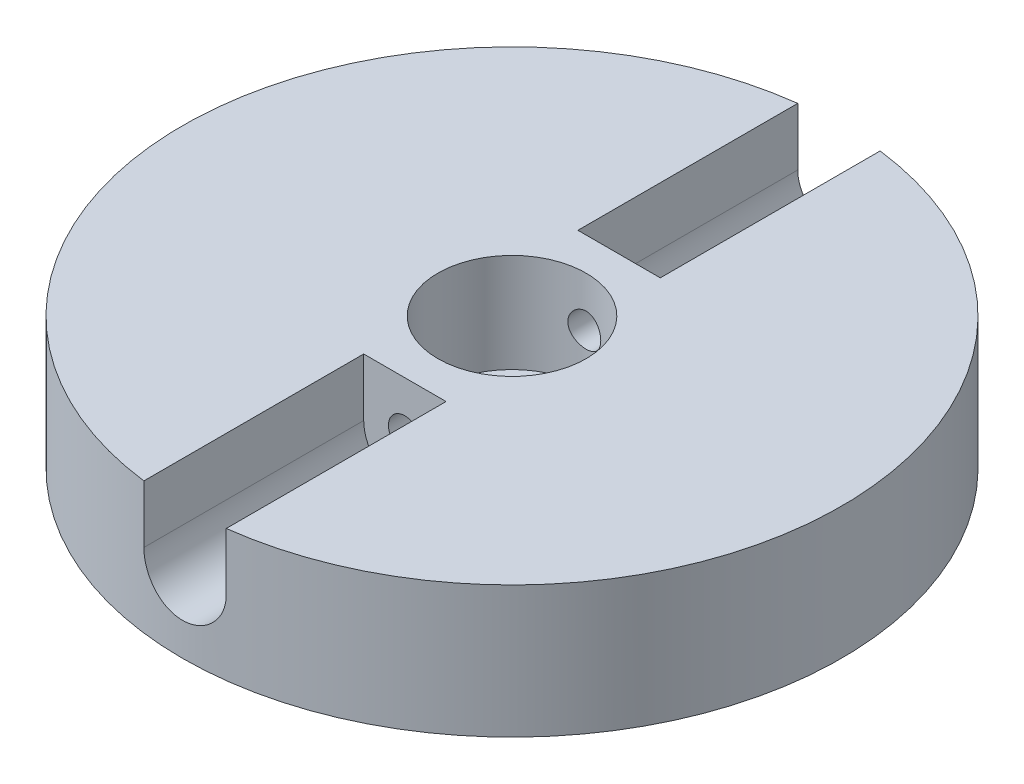
SolidWorks part; units mm, degrees
ref_plane "Front Plane" through (0, 0, 0) normal (0, 0, 1) x (1, 0, 0)
ref_plane "Top Plane" through (0, 0, 0) normal (0, 1, 0) x (1, 0, 0)
ref_plane "Right Plane" through (0, 0, 0) normal (1, 0, 0) x (0, 0, -1)
sketch "Sketch2" plane through (0, 0, 0) normal (0, 1, 0) x (1, 0, 0)
  circle A0 centre (0, 0) radius 20
  dimension "D1" = 40
extrude "Boss-Extrude1" add sketch "Sketch2" along normal blind 8
sketch "Sketch3" plane through (0, 8, 0) normal (0, 1, 0) x (1, 0, 0)
  circle A0 centre (0, 0) radius 12.5
  circle A1 centre (0, 0) radius 4.5
  dimension "D1" = 25
  dimension "D2" = 9
ref_plane "Plane1" through (0, 0, 4.5) normal (0, 0, 1) x (1, 0, 0)
sketch "Sketch7" plane through (0, 0, 4.5) normal (0, 0, 1) x (1, 0, 0)
  line L0 (0, 0) -> (0, 5)
  circle A0 centre (0, 5) radius 1
  dimension "D1" = 5
extrude "Cut-Extrude7" cut sketch "Sketch7" along normal through all both and the other way through all
ref_plane "Plane2" through (0, 0, 20) normal (0, 0, 1) x (1, 0, 0)
ref_plane "Plane3" through (0, 0, -6.5) normal (0, 0, 1) x (1, 0, 0)
sketch "Sketch9" plane through (0, 0, 20) normal (0, 0, 1) x (1, 0, 0)
  line L0 (2.5, 0) -> (2.5, 2)
  line L1 (0, 0) -> (2.5, 0)
  line L2 (0, 0) -> (0, 8)
  line L3 (0, 8) -> (2.5, 8)
  line L4 (2.5, 0) -> (2.5, 8)
  line L5 (0, 8) -> (-2.5, 8)
  line L6 (-2.5, 8) -> (-2.5, 0)
  line L7 (-2.5, 0) -> (0, 0)
  line L8 (2.5, 2) -> (-2.5, 2)
  arc A0 (-2.5, 4.5) -> (2.5, 4.5) centre (0, 4.5) ccw
  dimension "D6" = 2.5
  dimension "D1" = 2
  dimension "D2" = 8
  dimension "D3" = 2.5
  dimension "D4" = 8
  dimension "D5" = 2.5
extrude "Cut-Extrude8" cut sketch "Sketch9" against normal blind 13.5 contours L8 L2 L5 L6 | L8 L4 L3 L2
sketch "Sketch10" plane through (0, 0, -6.5) normal (0, 0, 1) x (1, 0, 0)
  line L1 (0, 0) -> (-2.5, 0)
  line L2 (0, 0) -> (0, 8)
  line L3 (0, 8) -> (-2.5, 8)
  line L4 (-2.5, 0) -> (-2.5, 8)
  line L5 (0, 0) -> (2.5, 0)
  line L6 (0, 0) -> (0, 8)
  line L7 (0, 8) -> (2.5, 8)
  line L8 (2.5, 0) -> (2.5, 8)
  arc A0 (-2.5, 4.5) -> (2.5, 4.5) centre (0, 4.5) ccw
  dimension "D5" = 4.5
  dimension "D1" = 8
  dimension "D2" = 2.5
  dimension "D3" = 2.5
  dimension "D4" = 8
extrude "Cut-Extrude15" cut sketch "Sketch10" against normal blind 15 contours L6 A0 L8 L7 | L4 A0 L6 L3
extrude "Cut-Extrude16" cut sketch "Sketch3" against normal blind 6 contours A1
sketch "Sketch12" plane through (0, 0, 0) normal (0, -1, 0) x (1, 0, 0)
  line L0 (0, 0) -> (-12, 0)
  line L1 (0, 0) -> (-8.4853, 8.4853)
  circle A0 centre (-8.4853, 8.4853) radius 1.5
  circle A1 centre (8.4853, 8.4853) radius 1.5
  circle A2 centre (8.4853, -8.4853) radius 1.5
  circle A3 centre (-8.4853, -8.4853) radius 1.5
  point P14 (0, 0)
  dimension "D4" = 4
  dimension "D1" = 12
  dimension "D2" = 12
  dimension "D3" = 45
extrude "Cut-Extrude17" cut sketch "Sketch12" against normal blind 3
